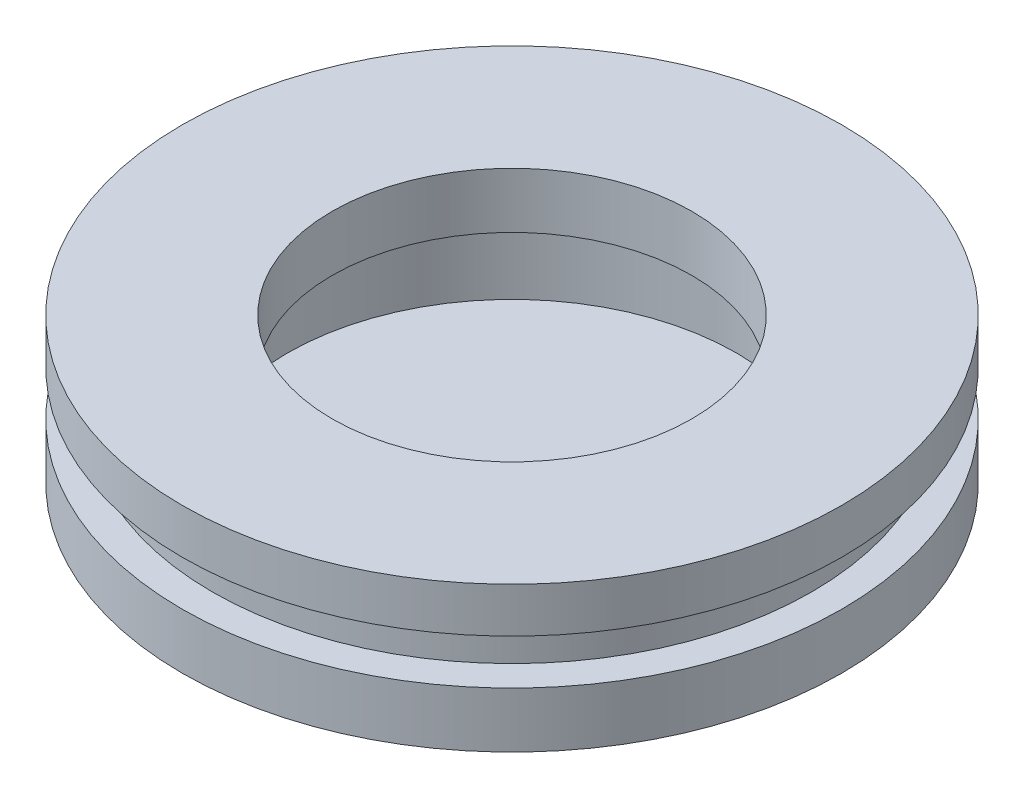
SolidWorks part; units mm, degrees
ref_plane "Plan de face" through (0, 0, 0) normal (0, 0, 1) x (1, 0, 0)
ref_plane "Plan de dessus" through (0, 0, 0) normal (0, 1, 0) x (1, 0, 0)
ref_plane "Plan de droite" through (0, 0, 0) normal (1, 0, 0) x (0, 0, -1)
sketch "Esquisse1" plane through (0, 0, 0) normal (0, 0, 1) x (1, 0, 0)
  line L0 (0, 0) -> (0, 8.8537)
  line L1 (0, 8.8537) -> (-11, 8.8537)
  line L2 (-11, 8.8537) -> (-11, 7.3537)
  line L3 (-11, 7.3537) -> (-10, 7.3537)
  line L4 (-10, 7.3537) -> (-10, 5.8537)
  line L5 (-10, 5.8537) -> (-11, 5.8537)
  line L6 (-11, 5.8537) -> (-11, 4.0037)
  line L7 (-11, 4.0037) -> (0, 0)
  dimension "D1" = 11
  dimension "D2" = 10
  dimension "D3" = 1.5
  dimension "D4" = 1.85
  dimension "D5" = 20
  dimension "D6" = 1.5
revolve "Révolution1" add sketch "Esquisse1" angle 360 about L0
sketch "Esquisse3" plane through (0, 0, 0) normal (0, 0, 1) x (1, 0, 0)
  line L0 (0, 0) -> (0, 11.1972) construction
  line L1 (-6, 10) -> (-6, 7)
  line L2 (-6, 7) -> (-7.5, 7)
  line L4 (-7.5, 7) -> (-7.5, 4.0037)
  line L5 (11, 4.0037) -> (-11, 4.0037) construction
  line L6 (-7.5, 4.0037) -> (0, 4.0037)
  line L7 (-6, 10) -> (0, 10)
  line L8 (0, 10) -> (0, 4.0037)
  dimension "D1" = 10
  dimension "D2" = 3
  dimension "D3" = 7.5
  dimension "D4" = 6
revolve "Enlèvement de matière-Révolution1" cut sketch "Esquisse3" angle 360 about L0
